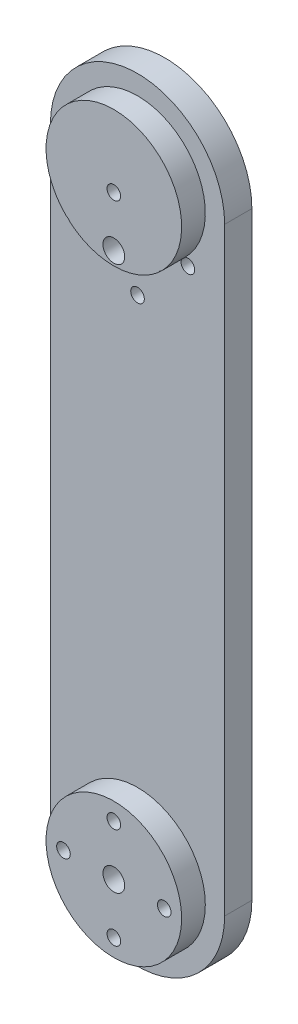
SolidWorks part; units mm, degrees
ref_plane "前视基准面" through (0, 0, 0) normal (0, 0, 1) x (1, 0, 0)
ref_plane "上视基准面" through (0, 0, 0) normal (0, 1, 0) x (1, 0, 0)
ref_plane "右视基准面" through (0, 0, 0) normal (1, 0, 0) x (0, 0, -1)
other "Configuration Table"
sketch "草图1" plane through (0, 0, 0) normal (0, 0, 1) x (1, 0, 0)
  circle A0 centre (0, 0) radius 24.9
  dimension "D1" = 49.8
extrude "凸台-拉伸1" add sketch "草图1" along normal blind 8.7
sketch "草图3" plane through (0, 0, 0) normal (0, 0, -1) x (-1, 0, 0)
  line L0 (0, 0) -> (0, 220) construction
  line L1 (-32, 0) -> (-32, 220)
  line L2 (32, 0) -> (32, 220)
  arc A0 (-32, 0) -> (32, 0) centre (0, 0) ccw
  arc A1 (32, 220) -> (-32, 220) centre (0, 220) ccw
  point P3 (0, 110)
  dimension "D2" = 32
  dimension "D1" = 220
extrude "凸台-拉伸2" add sketch "草图3" along normal blind 10
sketch "草图5" plane through (0, 0, 0) normal (0, 0, 1) x (1, 0, 0)
  circle A0 centre (0, 220) radius 24.9
  dimension "D1" = 49.8
extrude "凸台-拉伸4" add sketch "草图5" along normal up to surface (8.7 mm away) up to face at (24.9, 0, 8.7)
sketch "草图2" plane through (0, 0, 8.7) normal (0, 0, 1) x (1, 0, 0)
  circle A0 centre (0, 0) radius 25
  circle A1 centre (0, 0) radius 4
  circle A2 centre (0, 0) radius 18.5
  circle A3 centre (0, 18.5) radius 2.5
  circle A4 centre (-18.5, 0) radius 2.5
  circle A5 centre (18.5, 0) radius 2.5
  circle A6 centre (0, -18.5) radius 2.5
  circle A7 centre (0, 218.5) radius 2.5
  circle A8 centre (0, 200) radius 4
  circle A9 centre (0, 200) radius 18.5
  circle A10 centre (0, 181.5) radius 2.5
  circle A11 centre (0, 200) radius 25
  circle A12 centre (-18.5, 200) radius 2.5
  circle A13 centre (18.5, 200) radius 2.5
  point P24 (0, 200)
  dimension "D1" = 8
  dimension "D2" = 50
  dimension "D3" = 37
  dimension "D4" = 5
  dimension "D5" = 5
  dimension "D6" = 5
  dimension "D7" = 5
  dimension "D8" = 8
  dimension "D9" = 50
  dimension "D10" = 37
  dimension "D11" = 5
  dimension "D12" = 5
  dimension "D13" = 5
  dimension "D14" = 5
extrude "切除-拉伸1" cut sketch "草图2" against normal through all both and the other way through all contours A2 A4 | A2 A4 | A2 A6 | A2 A6 | A2 A5 | A2 A5 | A2 A3 | A2 A3 | A9 A7 | A7 A9 | A9 A12 | A9 A12 | A9 A10 | A9 A10 | A9 A13 | A9 A13 | A1 | A8
